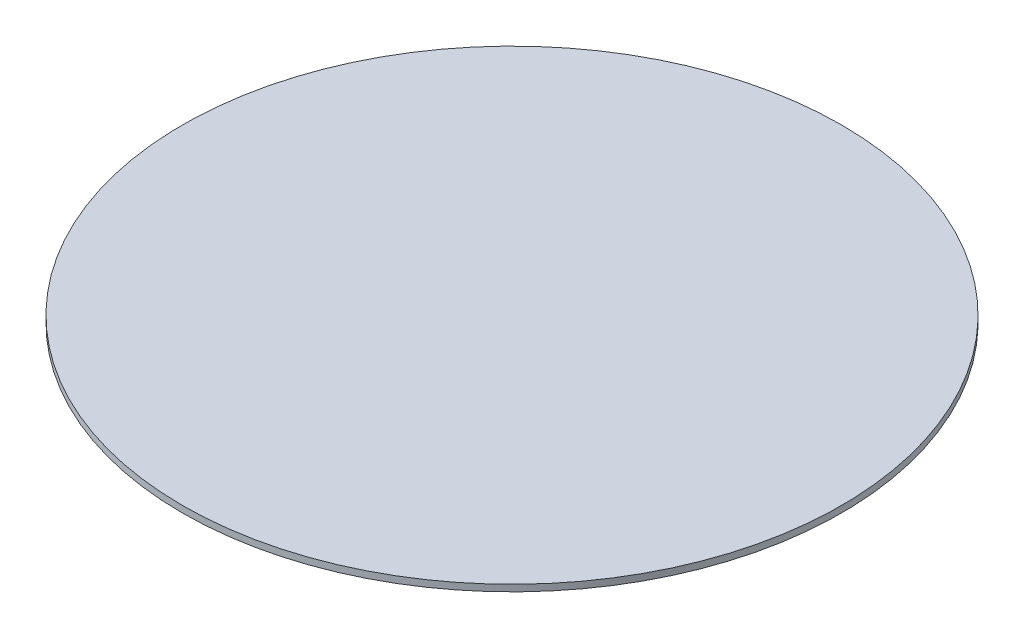
SolidWorks part; units mm, degrees
ref_plane "前基準面" through (0, 0, 0) normal (0, 0, 1) x (1, 0, 0)
ref_plane "上基準面" through (0, 0, 0) normal (0, 1, 0) x (1, 0, 0)
ref_plane "右基準面" through (0, 0, 0) normal (1, 0, 0) x (0, 0, -1)
sketch "草圖3" plane through (0, 0, 0) normal (0, 1, 0) x (1, 0, 0)
  line L0 (-21.15, 0) -> (-21.15, 15.5)
  line L11 (-21.15, 0) -> (-21.15, -15.5)
  line L12 (0, 21.15) -> (-15.5, 21.15)
  line L13 (0, 21.15) -> (15.5, 21.15)
  line L14 (21.15, 0) -> (21.15, 15.5)
  line L15 (21.15, 0) -> (21.15, -15.5)
  line L16 (0, -21.15) -> (-15.5, -21.15)
  line L17 (0, -21.15) -> (15.5, -21.15)
  line L18 (-21.15, -15.5) -> (-15.5, -21.15)
  line L19 (15.5, -21.15) -> (21.15, -15.5)
  line L20 (21.15, 15.5) -> (15.5, 21.15)
  line L21 (-15.5, 21.15) -> (-21.15, 15.5)
  point P0 (0, 0)
extrude "填料-伸長2" add sketch "草圖3" along normal blind 48
sketch "草圖4" plane through (0, 48, 0) normal (0, 1, 0) x (1, 0, 0)
  circle A0 centre (0, 0) radius 11
extrude "填料-伸長3" add sketch "草圖4" along normal blind 2
sketch "草圖5" plane through (0, 50, 0) normal (0, 1, 0) x (1, 0, 0)
  circle A0 centre (0, 0) radius 2.5
extrude "填料-伸長4" add sketch "草圖5" along normal blind 18
sketch "草圖6" plane through (0, 68, 0) normal (0, 1, 0) x (1, 0, 0)
  circle A0 centre (0, 0) radius 200
extrude "填料-伸長5" add sketch "草圖6" along normal blind 4
